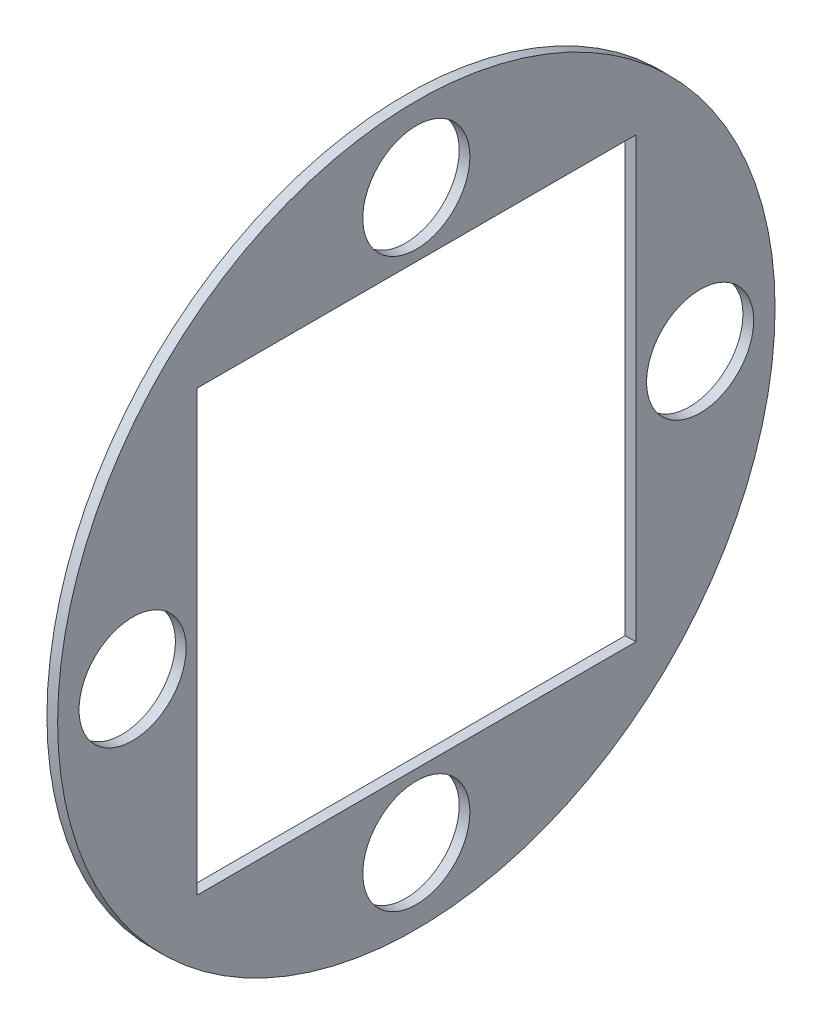
SolidWorks part; units mm, degrees
ref_plane "Front Plane" through (0, 0, 0) normal (1, 0, 0) x (0, 1, 0)
ref_plane "Top Plane" through (0, 0, 0) normal (0, 0, 1) x (0, 1, 0)
ref_plane "Right Plane" through (0, 0, 0) normal (0, 1, 0) x (-1, 0, 0)
sketch "Sketch2" plane through (0, 0, 0) normal (1, 0, 0) x (0, 1, 0)
  line L0 (0, 52.07) -> (0, 67.31)
  line L1 (52.07, -52.07) -> (-52.07, -52.07)
  line L2 (52.07, -52.07) -> (52.07, 52.07)
  line L3 (52.07, 52.07) -> (-52.07, 52.07)
  line L4 (-52.07, -52.07) -> (-52.07, 52.07)
  line L5 (52.07, -52.07) -> (-52.07, 52.07) construction
  line L6 (52.07, 52.07) -> (-52.07, -52.07) construction
  circle A0 centre (0, 0) radius 85.09
  circle A1 centre (0, 67.31) radius 12.7
  circle A2 centre (67.31, 0) radius 12.7
  circle A3 centre (0, -67.31) radius 12.7
  circle A4 centre (-67.31, 0) radius 12.7
  point P19 (0, 0)
  dimension "D1" = 170.18
  dimension "D5" = 25.4
  dimension "D2" = 104.14
  dimension "D3" = 104.14
  dimension "D4" = 15.24
  dimension "D6" = 4
extrude "Boss-Extrude1" add sketch "Sketch2" along normal blind 2.54 contours A0 | L2 L1 L4 L3 | A4 | A1 | A2 | A3
